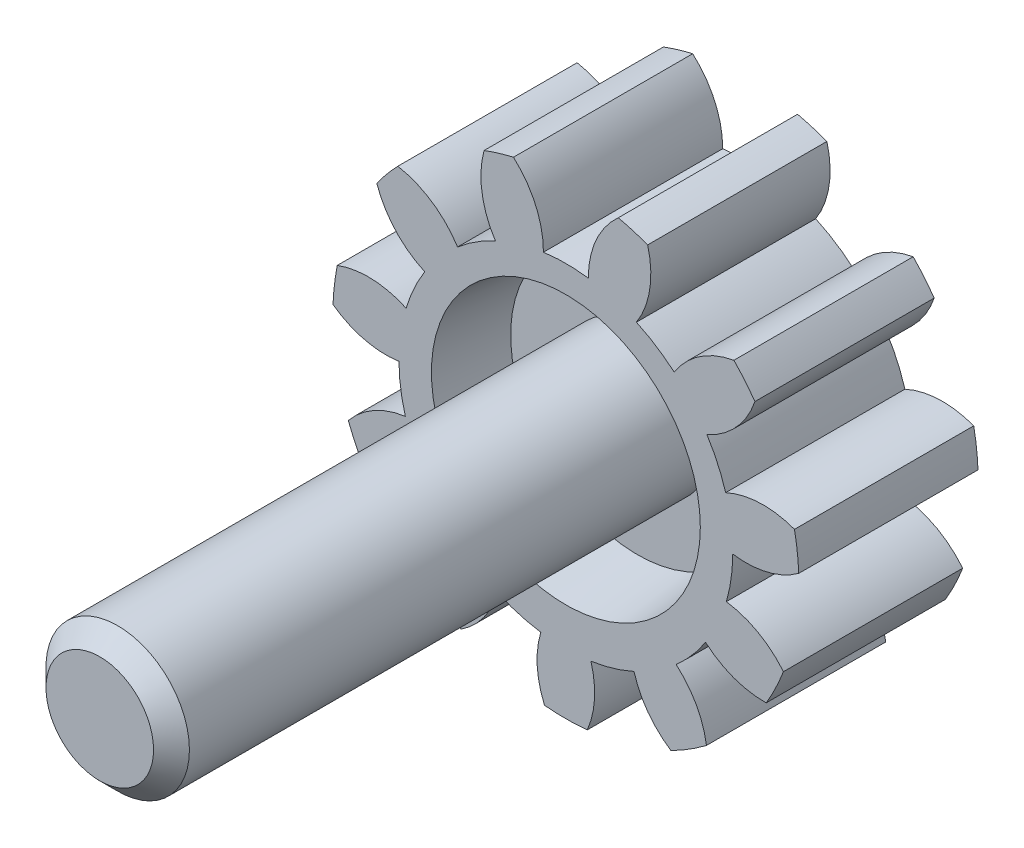
SolidWorks part; units mm, degrees
ref_plane "Спереди" through (0, 0, 0) normal (0, 0, 1) x (1, 0, 0)
ref_plane "Сверху" through (0, 0, 0) normal (0, 1, 0) x (1, 0, 0)
ref_plane "Справа" through (0, 0, 0) normal (1, 0, 0) x (0, 0, -1)
sketch "Эскиз3" plane through (0, 0, 0) normal (0, 0, 1) x (1, 0, 0)
  circle A0 centre (0, 0) radius 13
  dimension "D1" = 26
extrude "Бобышка-Вытянуть1" add sketch "Эскиз3" against normal blind 10
sketch "Эскиз4" plane through (0, 0, 0) normal (0, 0, 1) x (1, 0, 0)
  line L0 (0, 0) -> (0, 13) construction
  line L1 (0, 0) -> (-2.9244, 12.6668) construction
  line L2 (0, 0) -> (-2.0295, 14.4408) construction
  circle A0 centre (0, 0) radius 13 construction
  arc A1 (2.9244, 12.6668) -> (-2.9244, 12.6668) centre (0, 0) ccw
  arc A2 (1.2526, 8.9124) -> (-1.2526, 8.9124) centre (0, 0) ccw
  arc A3 (-1.2526, 8.9124) -> (-2.9244, 12.6668) centre (-6.2525, 8.9354) ccw
  arc A4 (1.2526, 8.9124) -> (2.9244, 12.6668) centre (6.2525, 8.9354) cw
  dimension "D3" = 9
  dimension "D4" = 5
  dimension "D1" = 8
  dimension "D2" = 13
extrude "Вырез-Вытянуть1" cut sketch "Эскиз4" against normal through all
pattern_circular "Круговой массив1" count 11 over 360 about axis through (0, -0.3135, 0) along (0, 0, 1) of "Вырез-Вытянуть1"
sketch "Эскиз5" plane through (0, 0, 0) normal (0, 0, 1) x (1, 0, 0)
  circle A0 centre (0, 0) radius 7.5
  dimension "D1" = 15
extrude "Вырез-Вытянуть2" cut sketch "Эскиз5" against normal blind 4 draft 6
sketch "Эскиз6" plane through (0, 0, -10) normal (0, 0, -1) x (-1, 0, 0)
  circle A0 centre (0, 0) radius 7.5
  dimension "D1" = 15
extrude "Вырез-Вытянуть3" cut sketch "Эскиз6" against normal blind 4 draft 6
sketch "Эскиз8" plane through (0, 0, -4) normal (0, 0, 1) x (1, 0, 0)
  circle A0 centre (0, 0) radius 4
  dimension "D1" = 8
extrude "Бобышка-Вытянуть3" add sketch "Эскиз8" along normal blind 30
chamfer "Фаска2" distance 1 angle 45 1 edges at (4, 0, 26)
